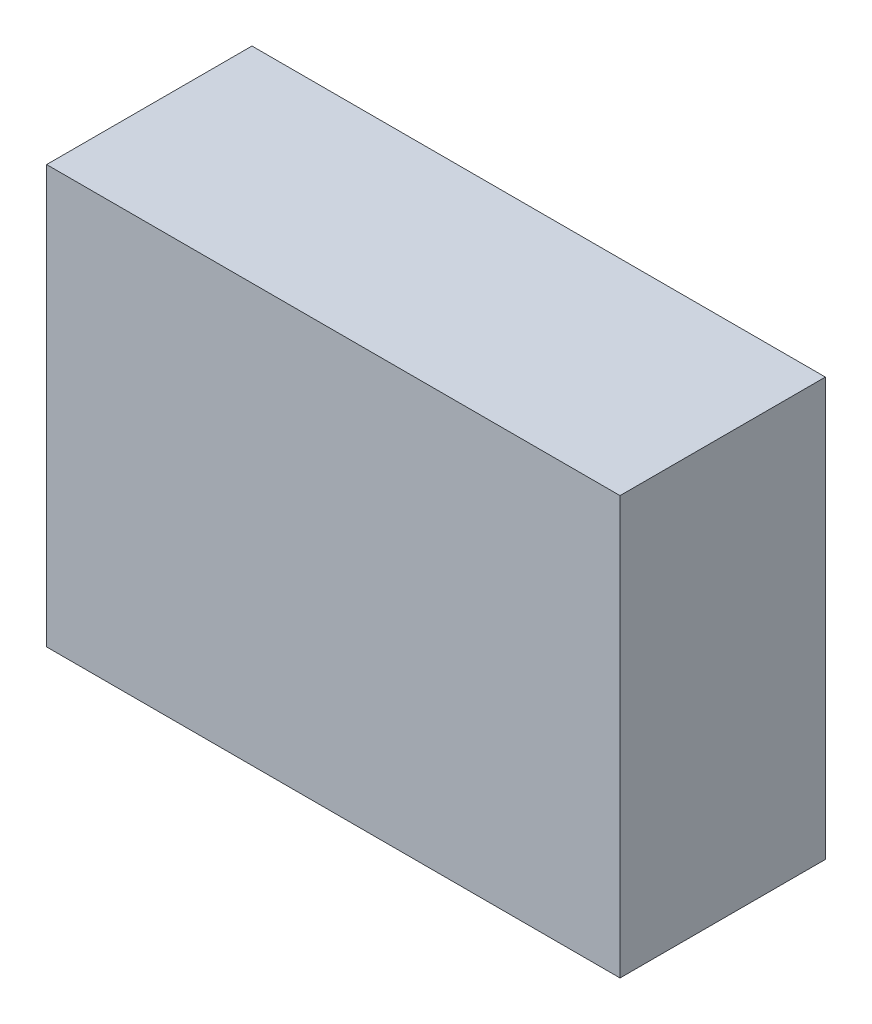
SolidWorks part; units mm, degrees
ref_plane "Front Plane" through (0, 0, 0) normal (0, 0, 1) x (1, 0, 0)
ref_plane "Top Plane" through (0, 0, 0) normal (0, 1, 0) x (1, 0, 0)
ref_plane "Right Plane" through (0, 0, 0) normal (1, 0, 0) x (0, 0, -1)
sketch "Sketch1" plane through (0, 0, 0) normal (0, 0, 1) x (1, 0, 0)
  line L1 (-10.5, 7.65) -> (10.5, 7.65)
  line L2 (-10.5, 7.65) -> (-10.5, -7.65)
  line L3 (-10.5, -7.65) -> (10.5, -7.65)
  line L4 (10.5, 7.65) -> (10.5, -7.65)
  line L5 (-10.5, 7.65) -> (10.5, -7.65) construction
  line L6 (-10.5, -7.65) -> (10.5, 7.65) construction
  point P0 (0, 0)
  dimension "D1" = 21
  dimension "D2" = 15.3
extrude "Boss-Extrude1" add sketch "Sketch1" along normal mid plane 7.52
